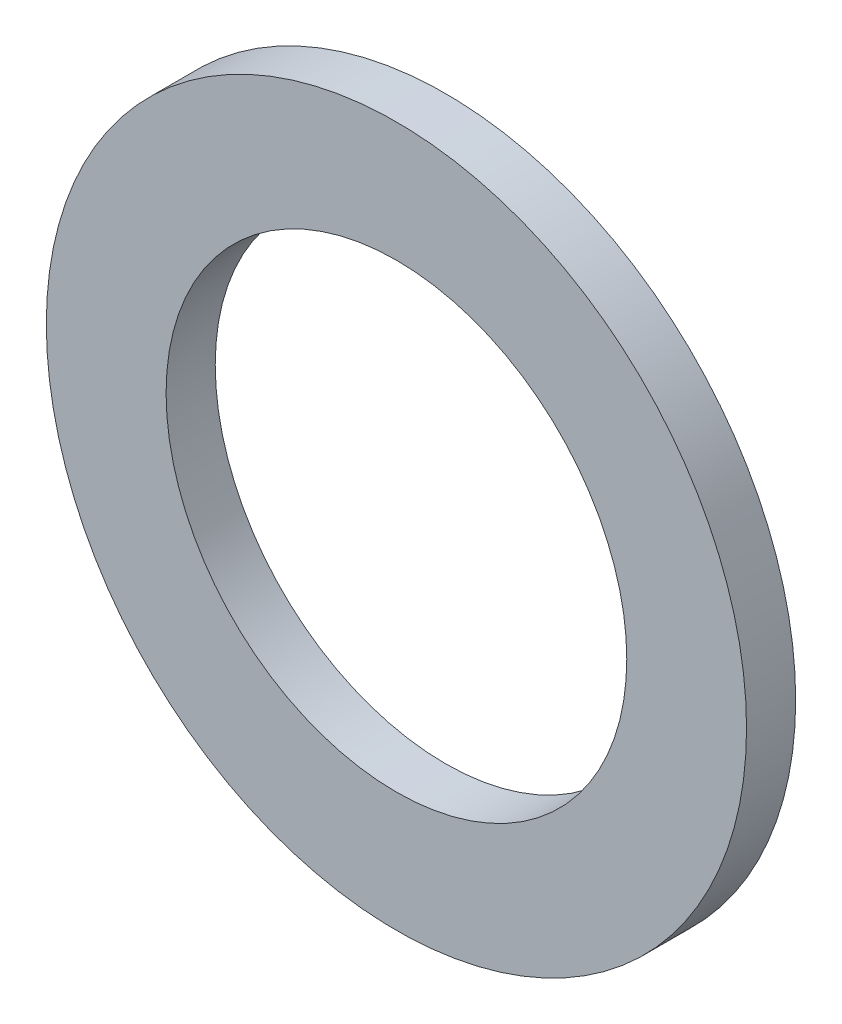
SolidWorks part; units mm, degrees
material "Nylon 101"
ref_plane "Front Plane" through (0, 0, 0) normal (0, 0, 1) x (1, 0, 0)
ref_plane "Top Plane" through (0, 0, 0) normal (0, 1, 0) x (1, 0, 0)
ref_plane "Right Plane" through (0, 0, 0) normal (1, 0, 0) x (0, 0, -1)
sketch "Sketch1" plane through (0, 0, 0) normal (0, 0, 1) x (1, 0, 0)
  circle A0 centre (0, 0) radius 7.239
  circle A1 centre (0, 0) radius 4.7625
  dimension "D1" = 14.478
  dimension "D2" = 9.525
extrude "Boss-Extrude1" add sketch "Sketch1" along normal blind 1.016
